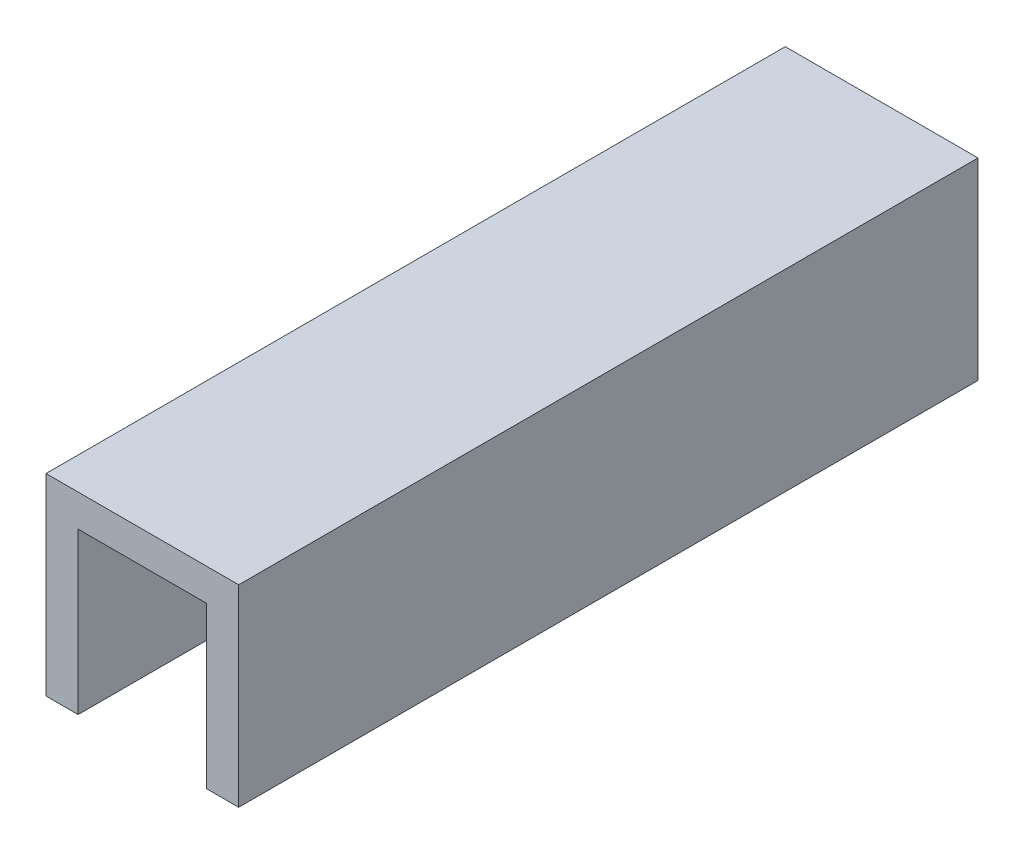
SolidWorks part; units mm, degrees
ref_plane "Front Plane" through (0, 0, 0) normal (0, 0, 1) x (1, 0, 0)
ref_plane "Top Plane" through (0, 0, 0) normal (0, 1, 0) x (1, 0, 0)
ref_plane "Right Plane" through (0, 0, 0) normal (1, 0, 0) x (0, 0, -1)
sketch "Sketch2" plane through (0, 0, 0) normal (0, 0, 1) x (1, 0, 0)
  line L0 (0, 0) -> (6.35, 0)
  line L1 (6.35, 0) -> (6.35, -7.9375)
  line L2 (6.35, -7.9375) -> (7.9375, -7.9375)
  line L3 (7.9375, -7.9375) -> (7.9375, 1.5875)
  line L4 (7.9375, 1.5875) -> (-1.5875, 1.5875)
  line L5 (-1.5875, 1.5875) -> (-1.5875, -7.9375)
  line L6 (-1.5875, -7.9375) -> (0, -7.9375)
  line L7 (0, -7.9375) -> (0, 0)
  dimension "D1" = 6.35
  dimension "D2" = 9.525
  dimension "D3" = 7.9375
  dimension "D4" = 9.525
sketch "Sketch3" plane through (0, 0, 0) normal (1, 0, 0) x (0, 0, -1)
  line L0 (0, 0) -> (-36.5379, 0)
  dimension "D1" = 36.5379
sweep "Sweep3" add profiles "Sketch2" path "Sketch3"
